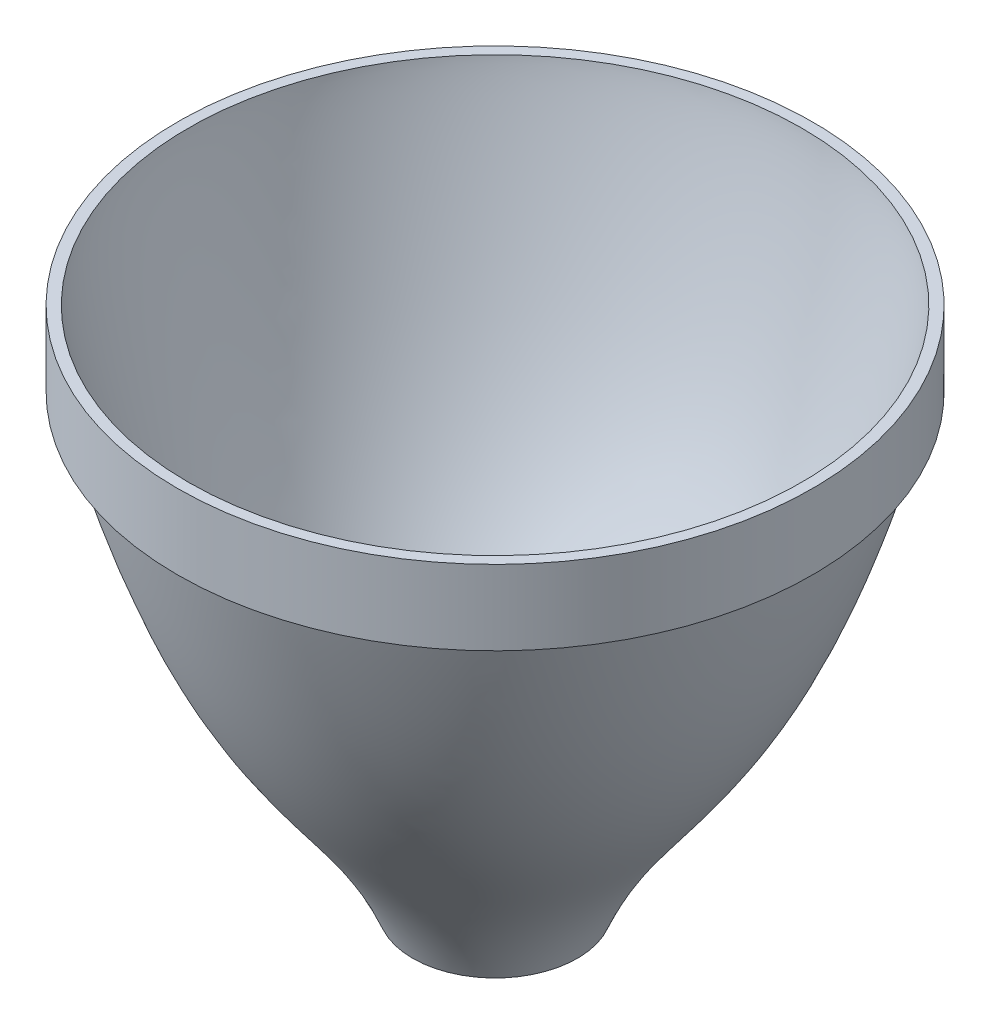
SolidWorks part; units mm, degrees
ref_plane "Płaszczyzna przednia" through (0, 0, 0) normal (0, 0, 1) x (1, 0, 0)
ref_plane "Płaszczyzna górna" through (0, 0, 0) normal (0, 1, 0) x (1, 0, 0)
ref_plane "Płaszczyzna prawa" through (0, 0, 0) normal (1, 0, 0) x (0, 0, -1)
sketch "Sketch1" plane through (0, 0, 0) normal (0, 0, 1) x (1, 0, 0)
  line L0 (-5.1658, 177.6565) -> (-5.1658, 45.3185)
  line L1 (-5.1658, 45.3185) -> (-2.6658, 45.3185)
  line L2 (-2.6658, 45.3185) -> (-2.6658, 176.1565)
  line L3 (-2.6658, 176.1565) -> (10.8342, 176.1565)
  line L4 (10.8342, 176.1565) -> (10.8342, 174.5528)
  line L5 (10.8342, 174.5528) -> (12.3342, 174.5528)
  line L6 (12.3342, 174.5528) -> (12.3342, 176.1565)
  line L8 (24.8342, 176.1565) -> (24.8342, 177.6565)
  line L10 (12.3342, 177.6565) -> (12.3342, 182.6565)
  line L11 (12.3342, 182.6565) -> (10.8342, 182.6565)
  line L12 (10.8342, 182.6565) -> (10.8342, 177.6565)
  line L13 (10.8342, 177.6565) -> (-5.1658, 177.6565)
  line L15 (24.8342, 148.4714) -> (24.8342, -40.5547) construction
  line L16 (10.8342, 177.6565) -> (10.8342, 176.1565)
  line L17 (-3.9845, 53.8719) -> (56.7742, 96.4156)
  line L21 (56.7742, 96.4156) -> (56.7742, 93.974)
  line L22 (56.7742, 93.974) -> (-3.4255, 51.8217)
  line L26 (18.8342, 86.6736) -> (17.445, 86.1079)
  line L30 (-2.6658, 126.4174) -> (-3.6326, 126.4174)
  line L32 (-2.6658, 133.1274) -> (-3.6326, 133.1274)
  line L33 (-3.6326, 133.1274) -> (-3.6326, 126.4174)
  line L34 (-2.6658, 126.2174) -> (-3.8326, 126.2174)
  line L35 (-3.8326, 126.2174) -> (-3.8326, 133.3274)
  line L36 (-3.8326, 133.3274) -> (-2.6658, 133.3274)
  line L37 (12.3342, 177.6565) -> (12.3342, 176.1565)
  spline S0 degree 3 poles (-2.6658, 133.1274) (-2.3289, 130.5698) (5.8169, 99.9377) (14.3451, 97.6992) (18.8342, 86.6736) knots 0 0 0 0 0.272542 1 1 1 1
  spline S1 degree 1 poles (-4.1529, 132.9315) (17.445, 86.1079) knots 0 0 1 1 construction
  spline S2 degree 3 poles (-4.1529, 132.9315) (-4.1286, 132.7468) (-4.0745, 132.3996) (-3.9156, 131.5398) (-3.6401, 130.2648) (-3.2392, 128.6059) (-2.8514, 127.1061) (-2.2724, 124.9534) (-1.3167, 121.6218) (0.154, 117.0029) (1.7366, 112.7061) (3.8504, 107.8349) (6.5061, 103.0056) (9.6132, 98.5782) (12.0285, 95.4515) (13.8207, 92.9255) (15.0961, 90.9232) (16.1074, 89.073) (16.8794, 87.4486) (17.2645, 86.5511) (17.445, 86.1079) knots 0 0 0 0 0.015625 0.03125 0.0625 0.09375 0.115853 0.131478 0.1875 0.25 0.3125 0.375 0.5 0.625 0.75 0.8125 0.875 0.9375 0.96875 1 1 1 1 only from (-2.6658, 126.4174) to (17.445, 86.1079)
  point P31 (0, 0)
  dimension "D1" = 2.5
  dimension "D2" = 0.2
  dimension "D3" = 1.5
  dimension "D4" = 5
  dimension "D5" = 1.5
  dimension "D6" = 30
  dimension "D7" = 6
  dimension "D10" = 0.2
  dimension "D11" = 0.2
  dimension "D12" = 7.11
  dimension "D9" = 1.5
revolve "Revolve1" add sketch "Sketch1" angle 360 about L15
